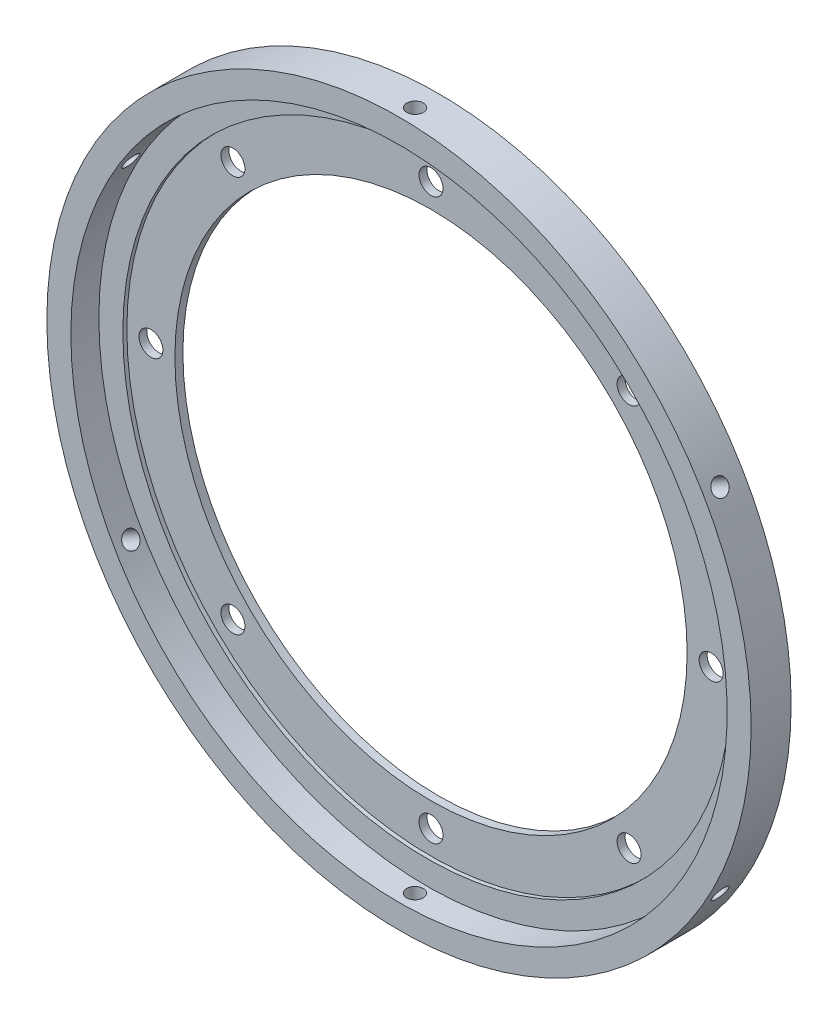
SolidWorks part; units mm, degrees
material "AISI Type 316L stainless steel"
ref_plane "Front Plane" through (0, 0, 0) normal (0, 0, 1) x (1, 0, 0)
ref_plane "Top Plane" through (0, 0, 0) normal (0, 1, 0) x (1, 0, 0)
ref_plane "Right Plane" through (0, 0, 0) normal (1, 0, 0) x (0, 0, -1)
sketch "Sketch1" plane through (0, 0, 0) normal (1, 0, 0) x (0, 0, -1)
  line L0 (0, 0) -> (-36.7756, 0) construction
  line L1 (0, 32) -> (0, 44)
  line L2 (0, 44) -> (-5, 44)
  line L3 (-5, 44) -> (-5, 41)
  line L4 (-5, 41) -> (-1.5, 41)
  line L5 (-1.5, 41) -> (-1.5, 38)
  line L6 (-1.5, 38) -> (-1, 38)
  line L7 (-1, 38) -> (-1, 32)
  line L8 (-1, 32) -> (0, 32)
  dimension "D1" = 64
  dimension "D2" = 76
  dimension "D3" = 82
  dimension "D4" = 88
  dimension "D5" = 1
  dimension "D6" = 1.5
  dimension "D7" = 5
revolve "Revolve1" add sketch "Sketch1" angle 360 about L0
hole_wizard "Ø3.0 (3) Diameter Hole1" positions "Sketch3" profile "Sketch2" hole size "Ø3.0" standard "Ansi Metric"
sketch "Sketch3" plane through (0, 0, 1) normal (0, 0, 1) x (1, 0, 0)
  point P0 (0, 35)
  dimension "D1" = 35
sketch "Sketch2" plane through (0, 35, 1) normal (1, 0, 0) x (0, -1, 0)
  line L0 (0, 0) -> (0, 2.4013)
  line L1 (0, 2.4013) -> (1.5, 1.5)
  line L2 (1.5, 1.5) -> (1.5, 0)
  line L5 (1.5, 0) -> (0, 0)
  line L10 (0, 2.4013) -> (-1.5, 1.5) construction
  line L11 (0, -6.35) -> (0, 107.95) construction
  dimension "Hole Dia." = 3
  dimension "Hole Depth" = 1.5
  dimension "Drill Angle" = 118
ref_axis "Axis1" through (0, 0, 5.25) along (0, 0, -1)
pattern_circular "CirPattern1" count 8 over 360 about axis through (0, 0, 0) along (0, 0, 1) of "Ø3.0 (3) Diameter Hole1"
hole_wizard "M2.5x0.45 Tapped Hole1" positions "3DSketch1" profile "Sketch4" tap size "M2.5x0.45" standard "Ansi Metric"
sketch3d "3DSketch1"
  line L4 (0, 0, 0) -> (0, 44, 0) construction
  line L5 (0, 44, 0) -> (0, 44, 3) construction
  line L7 (0, 0, 5.25) -> (0, 0, -0.25) construction
  circle A0 centre (0, 0, 0) radius 44 construction
  point P0 (0, 44, 3)
  point P20 (0, 0, -44)
  dimension "D1" = 3
sketch "Sketch4" plane through (0, 44, 3) normal (1, 0, 0) x (0, 0, 1)
  line L0 (0, 0) -> (0, 6.9659)
  line L1 (0, 6.9659) -> (1.025, 6.35)
  line L2 (1.025, 6.35) -> (1.025, 0)
  line L5 (1.025, 0) -> (0, 0)
  line L10 (0, 6.9659) -> (-1.025, 6.35) construction
  line L11 (0, -6.35) -> (0, 107.95) construction
  dimension "Tap Drill Dia." = 2.05
  dimension "Tap Drill Depth" = 6.35
  dimension "Drill Angle" = 118
pattern_circular "CirPattern2" count 6 over 360 about axis through (0, 0, 5.25) along (0, 0, -1) of "M2.5x0.45 Tapped Hole1"
